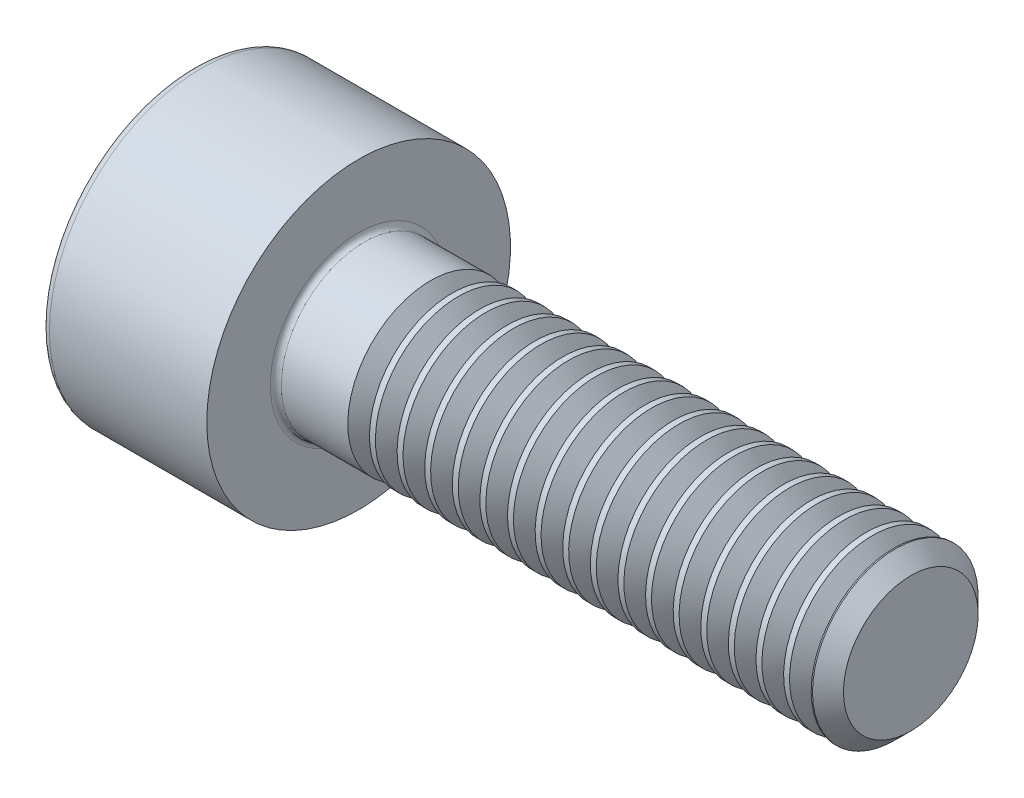
SolidWorks part; units mm, degrees
ref_plane "Plane1" through (0, 0, 0) normal (0, 0, 1) x (1, 0, 0)
ref_plane "Plane2" through (0, 0, 0) normal (0, 1, 0) x (1, 0, 0)
ref_plane "Plane3" through (0, 0, 0) normal (1, 0, 0) x (0, 0, -1)
sketch "BodySke" plane through (0, 0, 0) normal (0, 0, 1) x (1, 0, 0)
  line L0 (0, 0) -> (0, 2.75)
  line L1 (0, 2.75) -> (3, 2.75)
  line L2 (3, 2.75) -> (3, 1.5)
  line L3 (3, 1.5) -> (12.7195, 1.5)
  line L4 (13, 1.2195) -> (13, 0)
  line L5 (13, 0) -> (0, 0)
  line L6 (-31.75, 0) -> (127, 0) construction
  line L8 (13, 1.2195) -> (12.7195, 1.5)
  line L10 (13, -1.2195) -> (12.7195, -1.5) construction
  line L11 (3.5, 9.525) -> (3.5, 3.175) construction
  line L12 (3, 9.525) -> (3, 3.175) construction
  line L13 (-47, 9.525) -> (-47, 3.175) construction
  dimension "Diameter" = 3
  dimension "Head_ht" = 3
  dimension "Length" = 10
  dimension "Body_ch_ang" = 45
  dimension "Head_dia" = 5.5
  dimension "Minor_dia" = 2.439
  dimension "Advance" = 0.5
  dimension "Thread_nom" = 10
  dimension "Thread_length" = 60
revolve "Base-Revolve" add sketch "BodySke"
cosmetic thread "ThreadCosmetic" [suppressed]
fillet "Fillet1" radius 0.1 1 edges at (3, 0, 1.5)
fillet "Fillet2" radius 0.15 1 edges at (0, 0, 2.75)
sketch "Sketch2" plane through (0, 0, 0) normal (0, 0, 1) x (1, 0, 0)
  line L0 (0, 1.28) -> (1.3, 1.28)
  line L1 (1.3, 1.28) -> (2.039, 0)
  line L2 (-31.75, 0) -> (127, 0) construction
  line L3 (2.039, 0) -> (0, 0)
  line L4 (0, 0) -> (0, 1.28)
  line L6 (0, 0) -> (47.625, 0) construction
  dimension "D1" = 1.28
  dimension "D2" = 60
  dimension "Depth" = 1.3
revolve "Hex-PreBroach" cut sketch "Sketch2" angle 360 about L6
sketch "Sketch3" plane through (0, 0, 0) normal (-1, 0, 0) x (0, 0.5, 0.866)
  line L0 (0.739, 1.28) -> (-0.739, 1.28)
  line L1 (-0.739, 1.28) -> (-1.478, 0)
  line L2 (0.739, 1.28) -> (1.478, 0)
  line L3 (0.739, -1.28) -> (1.478, 0)
  line L4 (0.739, -1.28) -> (-0.739, -1.28)
  line L5 (-0.739, -1.28) -> (-1.478, 0)
  dimension "D1" = 1.28
  dimension "D2" = 1.28
  dimension "Hex_size" = 2.56
extrude "Hex" cut sketch "Sketch3" against normal blind 1.3
sketch "ThdSchSke" plane through (0, 0, 0) normal (0, 0, 1) x (1, 0, 0)
  line L0 (4.5, -1.2195) -> (4.3036, -1.5)
  line L1 (4.5, -1.2195) -> (4.6964, -1.5)
  line L2 (4.6964, -1.5) -> (4.6964, -1.875)
  line L3 (-3.175, 0) -> (5.1513, 0) construction
  line L4 (0, 2.6) -> (0, -2.6) construction
  line L5 (4.6964, -1.875) -> (4.3036, -1.875)
  line L6 (4.3036, -1.875) -> (4.3036, -1.5)
  dimension "Thread_minor" = 2.439
  dimension "Diameter" = 3
  dimension "Start" = 4.5
  dimension "SideAngle" = 55
  dimension "VeeAngle" = 70
  dimension "Overcut" = 3.75
revolve "ThreadSchematic" cut sketch "ThdSchSke" angle 360 about L3
pattern_linear "ThdSchPat" count 17 spacing 0.5 along (1, 0, 0) of "ThreadSchematic"
equation "\"D2@Sketch3\" = \"Hex_size@Sketch3\" / 2"
equation "\"D1@Sketch3\" = \"Hex_size@Sketch3\" / 2"
equation "\"D1@Sketch2\" = \"Hex_size@Sketch3\" / 2"
equation "\"Thread_minor@ThreadCosmetic\"  =  \"Minor_dia@BodySke\""
equation "\"Depth@Sketch2\" =  \"Key_eng@Hex\""
equation "\"Thread_length@ThreadCosmetic\" = ((sgn( (\"Length@BodySke\" - \"Advance@BodySke\" * 3.0) - \"Thread_nom@BodySke\" )-1)*( (\"Length@BodySke\" - \"Advance@BodySke\" * 3.0) - \"Thread_nom@BodySke\" ))/-2+ \"Thread_nom@BodySke\""
equation "\"Thread_minor@ThdSchSke\" = \"Minor_dia@BodySke\""
equation "\"Diameter@ThdSchSke\" = \"Diameter@BodySke\""
equation "\"Overcut@ThdSchSke\" = \"Diameter@BodySke\" * 1.25"
equation "\"Start@ThdSchSke\" = \"Head_ht@BodySke\" + \"Length@BodySke\" - \"Thread_length@ThreadCosmetic\"  '---Non-countersunk---"
equation "\"Num_threads@ThdSchPat\" = int( \"Thread_length@ThreadCosmetic\" / \"Advance@BodySke\" + 0.999 )  + 1"
equation "\"Advance@ThdSchPat\" = \"Thread_length@ThreadCosmetic\" /  (\"Num_threads@ThdSchPat\" - 1) 'relax it"
equation "\"Num_threads@ThdSchPat\" = \"Num_threads@ThdSchPat\" - sgn( \"Num_threads@ThdSchPat\" - 1) '---chamfered tips only---"
